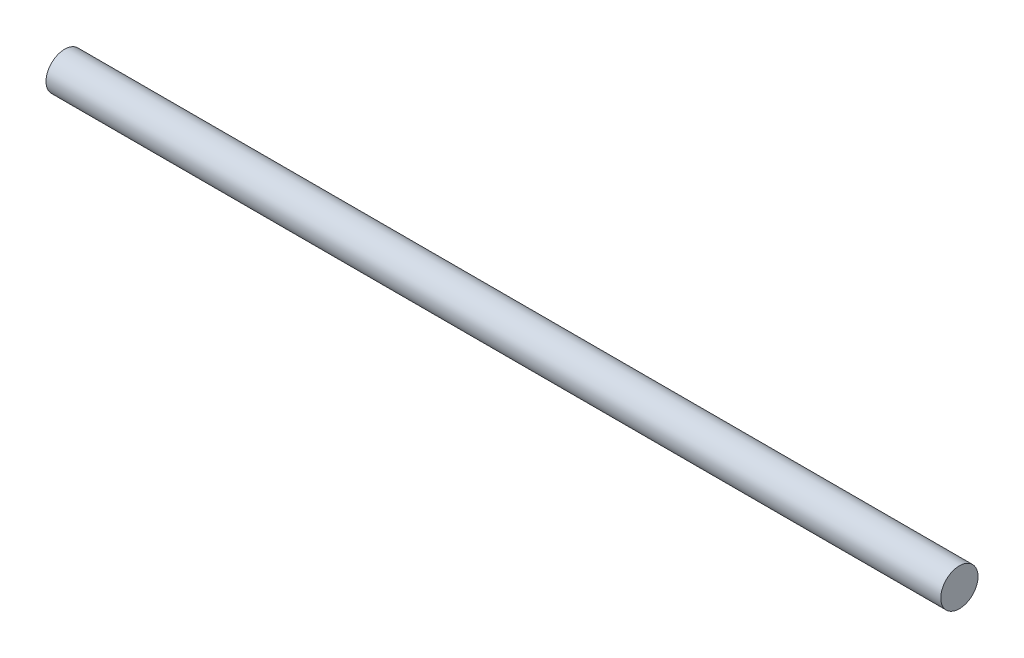
SolidWorks part; units mm, degrees
ref_plane "Front Plane" through (0, 0, 0) normal (0, 0, 1) x (1, 0, 0)
ref_plane "Top Plane" through (0, 0, 0) normal (0, 1, 0) x (1, 0, 0)
ref_plane "Right Plane" through (0, 0, 0) normal (1, 0, 0) x (0, 0, -1)
sketch "Sketch2" plane through (0, 0, 0) normal (1, 0, 0) x (0, 0, -1)
  circle A0 centre (0, 0) radius 3.175
extrude "Boss-Extrude1" add sketch "Sketch2" along normal blind 152.4
